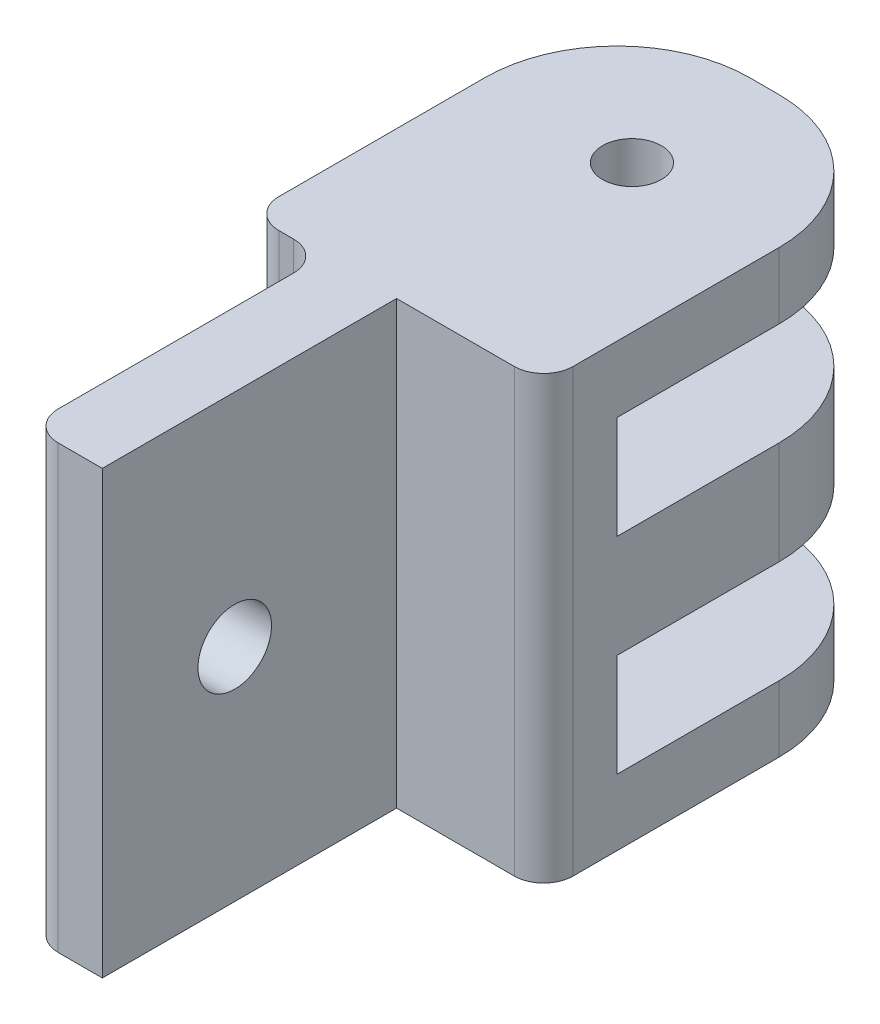
SolidWorks part; units mm, degrees
ref_plane "Front Plane" through (0, 0, 0) normal (0, 0, 1) x (1, 0, 0)
ref_plane "Top Plane" through (0, 0, 0) normal (0, 1, 0) x (1, 0, 0)
ref_plane "Right Plane" through (0, 0, 0) normal (1, 0, 0) x (0, 0, -1)
sketch "Sketch1" plane through (0, 0, 0) normal (0, 0, 1) x (1, 0, 0)
  line L1 (-10, -15) -> (10, -15)
  line L2 (-10, -15) -> (-10, 15)
  line L3 (-10, 15) -> (10, 15)
  line L4 (10, -15) -> (10, 15)
  line L5 (-10, -15) -> (10, 15) construction
  line L6 (-10, 15) -> (10, -15) construction
  point P0 (0, 0)
  dimension "D1" = 30
  dimension "D2" = 20
extrude "Boss-Extrude1" add sketch "Sketch1" along normal blind 25
sketch "Sketch2" plane through (0, 0, 0) normal (0, 0, -1) x (-1, 0, 0)
  line L0 (-10, -15) -> (-10, 15) construction
  line L1 (-10, 10.5) -> (10, 10.5)
  line L2 (-10, 10.5) -> (-10, 3.5)
  line L3 (-10, 3.5) -> (10, 3.5)
  line L4 (10, 10.5) -> (10, 3.5)
  line L5 (10, 15) -> (10, -15) construction
  line L6 (-10, 15) -> (10, 15) construction
  line L7 (10, -3.5025) -> (-10, -3.5025)
  line L8 (10, -3.5025) -> (10, -10.5)
  line L9 (10, -10.5) -> (-10, -10.5)
  line L10 (-10, -3.5025) -> (-10, -10.5)
  line L11 (10, -15) -> (-10, -15) construction
  dimension "D1" = 4.5
  dimension "D2" = 4.5
  dimension "D3" = 6.9975
  dimension "D4" = 7
extrude "Cut-Extrude1" cut sketch "Sketch2" against normal blind 20
sketch "Sketch3" plane through (0, 0, 25) normal (0, 0, 1) x (1, 0, 0)
  line L6 (0, -15) -> (-5, -15)
  line L7 (0, -15) -> (0, 15)
  line L8 (0, 15) -> (-5, 15)
  line L9 (-5, -15) -> (-5, 15)
  point P4 (0, 0)
  dimension "D1" = 5
  dimension "D2" = 30
extrude "Boss-Extrude3" add sketch "Sketch3" along normal blind 20
sketch "Sketch5" plane through (0, 0, 0) normal (1, 0, 0) x (0, 0, -1)
  line L1 (-45, -15) -> (-45, 15) construction
  circle A0 centre (-36, 0) radius 2.5
  dimension "D1" = 5
  dimension "D2" = 9
extrude "Cut-Extrude2" cut sketch "Sketch5" against normal blind 16 and the other way blind 13
fillet "Fillet1" radius 9 6 edges at (10, -12.75, 0) (-10, -12.75, 0) (-10, -0.0012, 0) (-10, 12.75, 0) (10, -0.0012, 0) (10, 12.75, 0)
sketch "Sketch6" plane through (0, 15, 0) normal (0, 1, 0) x (1, 0, 0)
  circle A0 centre (0, -9) radius 2
  dimension "D1" = 4
extrude "Cut-Extrude3" cut sketch "Sketch6" against normal blind 33 and the other way blind 11
fillet "Fillet2" radius 2 2 edges at (-10, 0, 25) (-5, 0, 25)
fillet "Fillet3" radius 2 1 edges at (10, 0, 25)
fillet "Fillet4" radius 2 1 edges at (-5, 0, 45)
